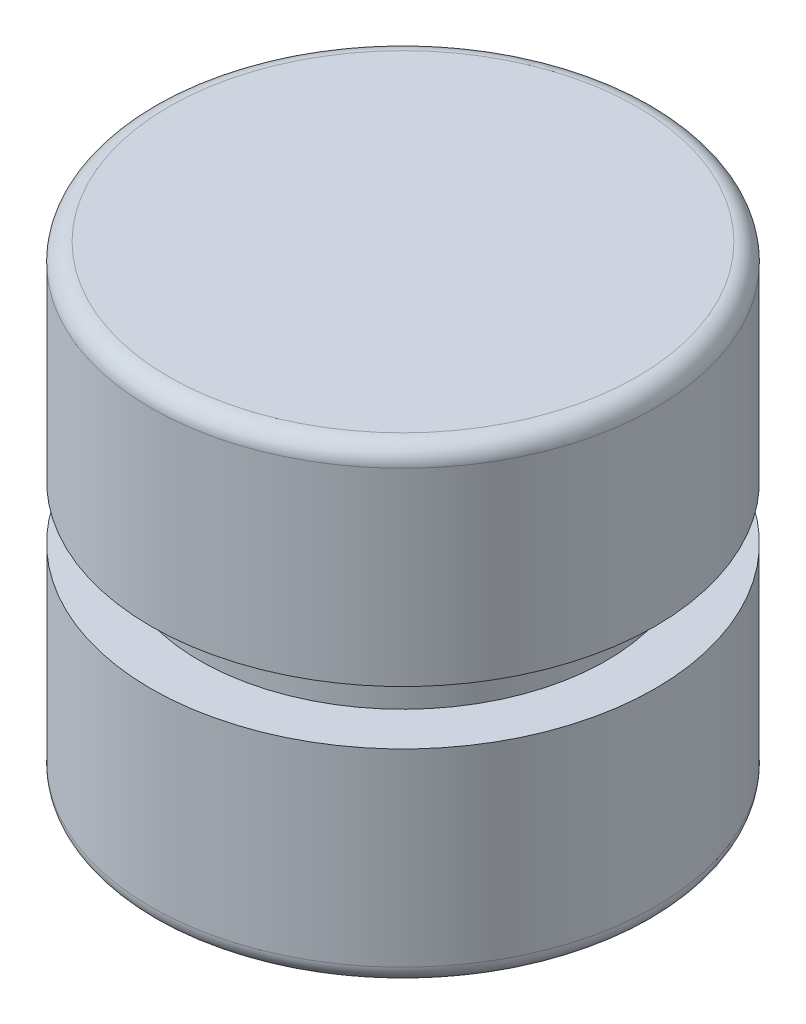
SolidWorks part; units mm, degrees
ref_plane "Front Plane" through (0, 0, 0) normal (0, 0, 1) x (1, 0, 0)
ref_plane "Top Plane" through (0, 0, 0) normal (0, 1, 0) x (1, 0, 0)
ref_plane "Right Plane" through (0, 0, 0) normal (1, 0, 0) x (0, 0, -1)
sketch "Sketch1" plane through (0, 0, 0) normal (0, 0, 1) x (1, 0, 0)
  line L0 (4.445, 0) -> (4.445, 12.7)
  line L1 (4.445, 12.7) -> (0, 12.7)
  line L3 (0, 16.51) -> (8.89, 16.51)
  line L4 (8.89, 16.51) -> (8.89, 9.2075)
  line L5 (8.89, 0) -> (4.445, 0)
  line L6 (8.89, 9.2075) -> (7.1755, 9.2075)
  line L7 (7.1755, 9.2075) -> (7.1755, 7.3025)
  line L8 (7.1755, 7.3025) -> (8.89, 7.3025)
  line L9 (8.89, 7.3025) -> (8.89, 0)
  line L10 (0, 0) -> (0, 16.51) construction
  line L11 (0, 16.51) -> (0, 12.7)
  point P12 (0, 8.255)
  point P13 (7.1755, 8.255)
  dimension "D1" = 8.89
  dimension "D2" = 16.51
  dimension "D3" = 4.445
  dimension "D4" = 1.905
  dimension "D5" = 2.7305
  dimension "D6" = 12.7
revolve "Revolve1" add sketch "Sketch1" angle 360 about L10
fillet "Fillet1" radius 0.635 2 edges at (0, 0, -8.89) (0, 16.51, -8.89)
